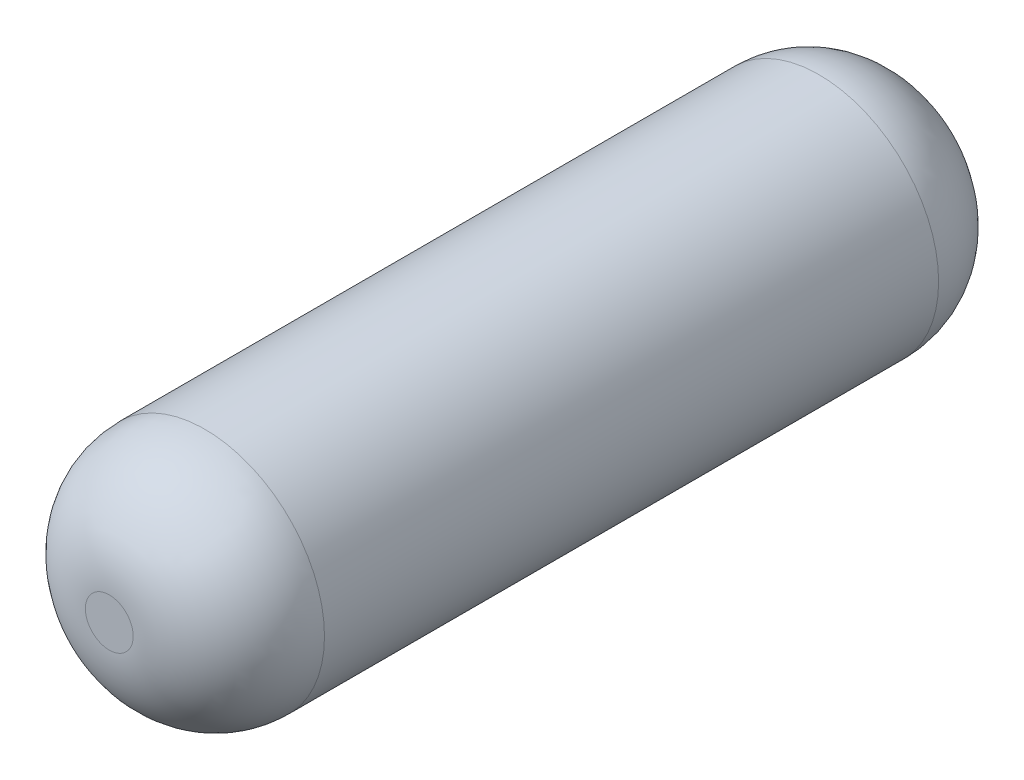
SolidWorks part; units mm, degrees
material "Parachute"
ref_plane "Front Plane" through (0, 0, 0) normal (0, 0, 1) x (1, 0, 0)
ref_plane "Top Plane" through (0, 0, 0) normal (0, 1, 0) x (1, 0, 0)
ref_plane "Right Plane" through (0, 0, 0) normal (1, 0, 0) x (0, 0, -1)
sketch "Sketch1" plane through (0, 0, 0) normal (0, 0, 1) x (1, 0, 0)
  circle A0 centre (0, 0) radius 60.325
  dimension "D1" = 120.65
extrude "Extrude1" add sketch "Sketch1" along normal blind 406.4
fillet "Fillet1" radius 48.26 2 edges at (60.325, 0, 0) (60.325, 0, 406.4)
